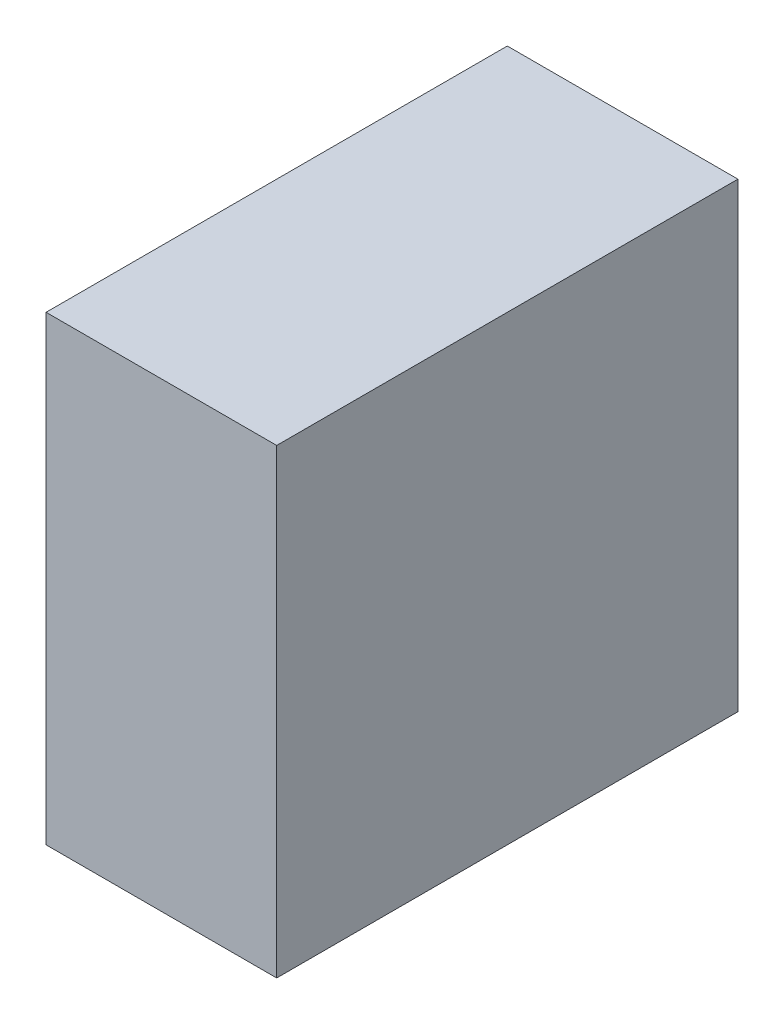
SolidWorks part; units mm, degrees
ref_plane "Front Plane" through (0, 0, 0) normal (0, 0, 1) x (1, 0, 0)
ref_plane "Top Plane" through (0, 0, 0) normal (0, 1, 0) x (1, 0, 0)
ref_plane "Right Plane" through (0, 0, 0) normal (1, 0, 0) x (0, 0, -1)
sketch "Sketch1" plane through (0, 0, 0) normal (0, 0, 1) x (1, 0, 0)
  line L1 (-15, -30) -> (15, -30)
  line L2 (-15, -30) -> (-15, 30)
  line L3 (-15, 30) -> (15, 30)
  line L4 (15, -30) -> (15, 30)
  line L5 (-15, -30) -> (15, 30) construction
  line L6 (-15, 30) -> (15, -30) construction
  point P0 (0, 0)
  dimension "D1" = 60
  dimension "D2" = 30
extrude "Boss-Extrude1" add sketch "Sketch1" along normal mid plane 60
